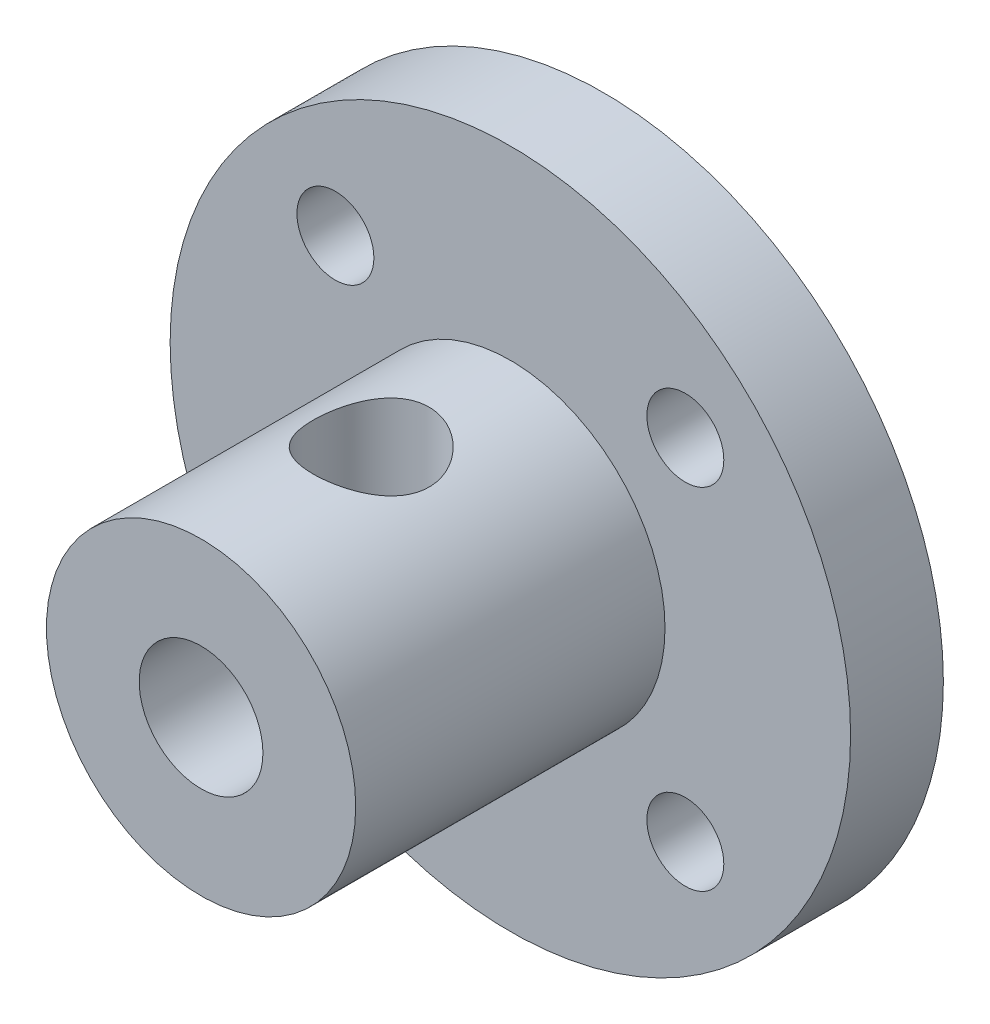
SolidWorks part; units mm, degrees
ref_plane "Front Plane" through (0, 0, 0) normal (0, 0, 1) x (1, 0, 0)
ref_plane "Top Plane" through (0, 0, 0) normal (0, 1, 0) x (1, 0, 0)
ref_plane "Right Plane" through (0, 0, 0) normal (1, 0, 0) x (0, 0, -1)
sketch "Sketch2" plane through (0, 0, 0) normal (0, 0, 1) x (1, 0, 0)
  line L1 (-5.6569, -5.6569) -> (5.6569, -5.6569) construction
  line L2 (-5.6569, -5.6569) -> (-5.6569, 5.6569) construction
  line L3 (-5.6569, 5.6569) -> (5.6569, 5.6569) construction
  line L4 (5.6569, -5.6569) -> (5.6569, 5.6569) construction
  line L5 (-5.6569, -5.6569) -> (5.6569, 5.6569) construction
  line L6 (-5.6569, 5.6569) -> (5.6569, -5.6569) construction
  circle A0 centre (0, 0) radius 11
  circle A1 centre (0, 0) radius 2
  circle A10 centre (-5.6569, 5.6569) radius 1.2442
  circle A11 centre (5.6569, 5.6569) radius 1.2442
  circle A12 centre (5.6569, -5.6569) radius 1.2442
  circle A13 centre (-5.6569, -5.6569) radius 1.2442
  point P15 (0, 0)
  dimension "D1" = 16
  dimension "D2" = 22
  dimension "D3" = 4
  dimension "D4" = 2.4883
extrude "Boss-Extrude1" add sketch "Sketch2" along normal blind 3
sketch "Sketch3" plane through (0, 0, 3) normal (0, 0, 1) x (1, 0, 0)
  circle A0 centre (0, 0) radius 5
  circle A2 centre (0, 0) radius 2
  dimension "D1" = 10
  dimension "D2" = 4
extrude "Boss-Extrude3" add sketch "Sketch3" along normal blind 10
sketch "Sketch6" plane through (0, 0, 0) normal (0, 1, 0) x (1, 0, 0)
  line L0 (-5, -3) -> (5, -3) construction
  circle A0 centre (0, -7.5) radius 1.875
  point P5 (0, 0)
  dimension "D1" = 3.75
  dimension "D2" = 4.5
extrude "Cut-Extrude2" cut sketch "Sketch6" against normal blind 3.2 from offset 5
sketch "Sketch10" plane through (0, 0, 0) normal (0, 1, 0) x (1, 0, 0)
  circle A0 centre (0, -7.5) radius 1.5
  dimension "D1" = 3
extrude "Cut-Extrude3" cut sketch "Sketch10" along normal blind 3
